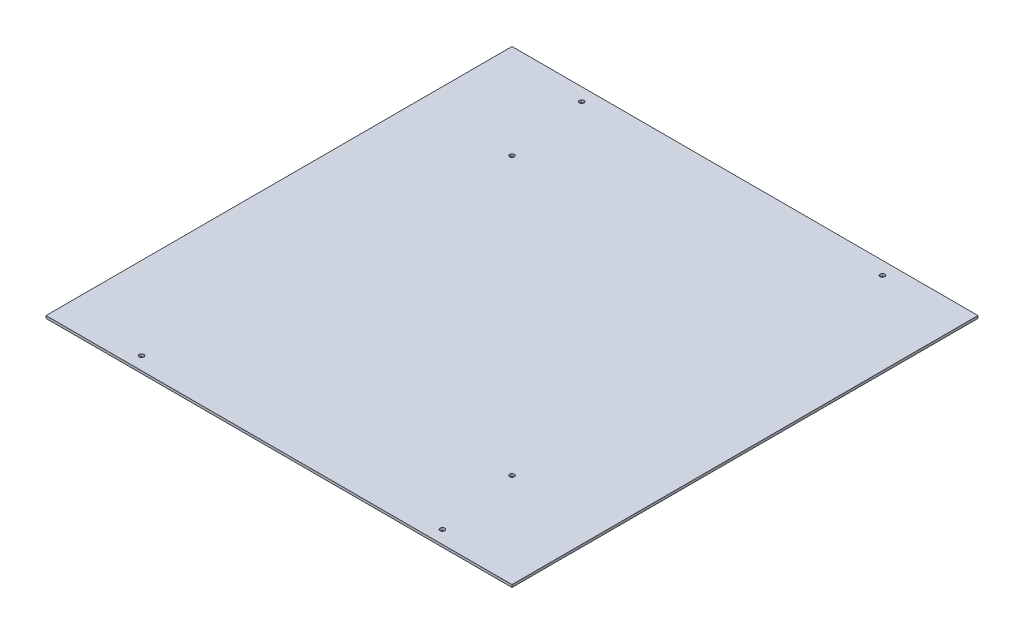
SolidWorks part; units mm, degrees
ref_plane "Front Plane" through (0, 0, 0) normal (0, 0, 1) x (1, 0, 0)
ref_plane "Top Plane" through (0, 0, 0) normal (0, 1, 0) x (1, 0, 0)
ref_plane "Right Plane" through (0, 0, 0) normal (1, 0, 0) x (0, 0, -1)
sketch "Sketch1" plane through (0, 0, 0) normal (0, 1, 0) x (1, 0, 0)
  line L1 (0, 0) -> (350, 0)
  line L2 (0, 0) -> (0, 350)
  line L3 (0, 350) -> (350, 350)
  line L4 (350, 0) -> (350, 350)
  line L5 (0, 0) -> (350, 350) construction
  line L6 (0, 350) -> (350, 0) construction
  point P4 (175, 175)
  dimension "D1" = 350
  dimension "D2" = 350
extrude "Boss-Extrude1" add sketch "Sketch1" along normal blind 1.9
sketch "Sketch2" plane through (0, 1.9, 0) normal (0, 1, 0) x (1, 0, 0)
  line L0 (277.7699, 72.2374) -> (281.4905, 68.5169) construction
  line L1 (0, 350) -> (0, 0) construction
  line L2 (0, 0) -> (350, 0) construction
  line L3 (350, 0) -> (350, 350) construction
  line L4 (350, 350) -> (0, 350) construction
  line L5 (71, 279) -> (71, 71) construction
  line L10 (68.4831, 281.5168) -> (72.2375, 277.7626) construction
  line L11 (71, 71) -> (279.0074, 71) construction
  line L12 (279.0074, 71) -> (279.0074, 279) construction
  line L13 (279.0074, 279) -> (71, 279) construction
  circle A0 centre (62, 340.25) radius 1.75
  circle A1 centre (288, 340.25) radius 1.75
  circle A2 centre (62, 9.75) radius 1.75
  circle A3 centre (288, 9.75) radius 1.75
  circle A4 centre (71, 279) radius 1.75
  circle A5 centre (279.0074, 71) radius 1.75
  point P24 (174.9887, 175.015)
  dimension "D1" = 3.5
  dimension "D2" = 3.5
  dimension "D3" = 3.5
  dimension "D4" = 3.5
  dimension "D6" = 9.75
  dimension "D13" = 3.5
  dimension "D14" = 3.5
  dimension "D5" = 62
  dimension "D7" = 9.75
  dimension "D8" = 62
  dimension "D9" = 62
  dimension "D10" = 9.75
  dimension "D11" = 62
  dimension "D12" = 9.75
  dimension "D15" = 294.1616
  dimension "D17" = 71
  dimension "D18" = 71
  dimension "D19" = 71
  dimension "D20" = 3.5594
extrude "Cut-Extrude2" cut sketch "Sketch2" against normal through all
